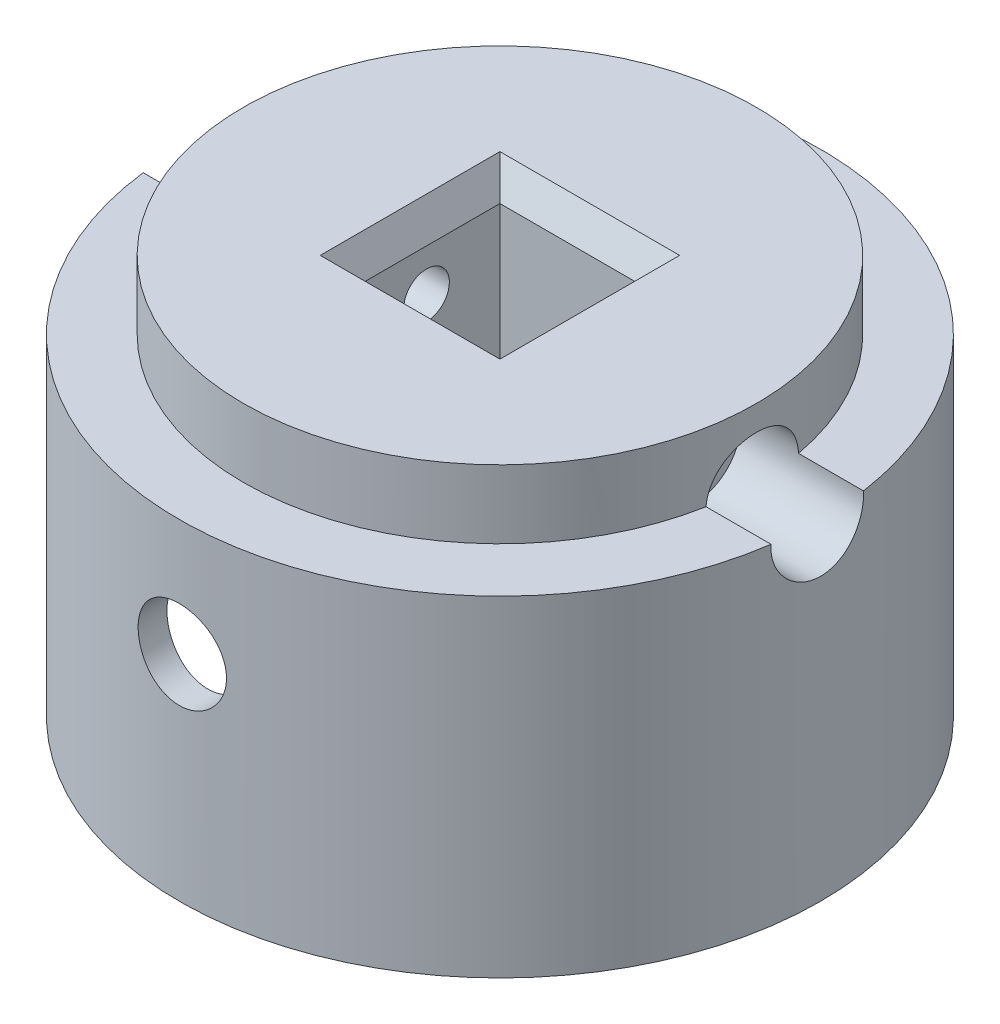
SolidWorks part; units mm, degrees
ref_plane "Спереди" through (0, 0, 0) normal (0, 0, 1) x (1, 0, 0)
ref_plane "Сверху" through (0, 0, 0) normal (0, 1, 0) x (1, 0, 0)
ref_plane "Справа" through (0, 0, 0) normal (1, 0, 0) x (0, 0, -1)
sketch "Sketch1" plane through (0, 0, 0) normal (0, 1, 0) x (1, 0, 0)
  circle A0 centre (0, 0) radius 22.5
  dimension "D1" = 45
extrude "Boss-Extrude1" add sketch "Sketch1" along normal blind 28
sketch "Sketch2" plane through (0, 0, 0) normal (0, -1, 0) x (1, 0, 0)
  line L1 (5.15, 5.15) -> (-5.15, 5.15)
  line L2 (5.15, 5.15) -> (5.15, -5.15)
  line L3 (5.15, -5.15) -> (-5.15, -5.15)
  line L4 (-5.15, 5.15) -> (-5.15, -5.15)
  line L5 (5.15, 5.15) -> (-5.15, -5.15) construction
  line L6 (5.15, -5.15) -> (-5.15, 5.15) construction
  point P0 (0, 0)
  dimension "D1" = 10.3
extrude "Cut-Extrude2" cut sketch "Sketch2" against normal through all
shell "Shell3" thickness 2
sketch "Sketch3" plane through (0, 0, 7.15) normal (0, 0, 1) x (1, 0, 0)
  line L0 (0, 26) -> (0, 0) construction
  line L1 (7.15, 26) -> (-7.15, 26) construction
  line L2 (7.15, 0) -> (-7.15, 0) construction
  line L3 (-22.5, 0) -> (22.5, 0) construction
  circle A0 centre (0, 15) radius 3.1
  dimension "D1" = 6.2
  dimension "D2" = 15
extrude "Cut-Extrude3" cut sketch "Sketch3" along normal through all
chamfer "Chamfer1" distance 2 angle 30 4 edges at (-5.15, 28, 0) (0, 28, 5.15) (5.15, 28, 0) (0, 28, -5.15)
sketch "Sketch18" plane through (0, 26, 0) normal (0, -1, 0) x (1, 0, 0)
  line L0 (0, 0) -> (-18.4253, -8.9866) construction
  line L1 (0, 0) -> (-17.385, 10.8633) construction
  line L2 (0, 0) -> (0, -20.5) construction
  line L3 (-15.7289, -7.6715) -> (-18.4253, -8.9866)
  line L4 (-14.8408, 9.2736) -> (-17.385, 10.8633)
  circle A0 centre (0, 0) radius 20.5 construction
  arc A1 (-18.4253, -8.9866) -> (-17.385, 10.8633) centre (0, 0) cw
  arc A2 (-14.8408, 9.2736) -> (-15.7289, -7.6715) centre (0, 0) ccw
  dimension "D1" = 64
  dimension "D2" = 58
  dimension "D3" = 3
extrude "Boss-Extrude8" add sketch "Sketch18" along normal offset from surface (23 mm away) 3 up to face at (0, 0, 20.5)
sketch "Sketch9" plane through (0, 0, 0) normal (0, -1, 0) x (1, 0, 0)
  line L0 (0, -7.15) -> (0, -20.5) construction
  line L2 (2.0571, -22.4058) -> (-16.5967, -15.1921)
  line L3 (-16.5967, -15.1921) -> (-17.6788, -17.9902)
  line L4 (-17.6788, -17.9902) -> (0.975, -25.2038)
  line L5 (0.975, -25.2038) -> (2.0571, -22.4058)
  line L6 (-7.15, -7.15) -> (7.15, -7.15) construction
  line L7 (2.0571, -22.4058) -> (0, -7.15) construction
  circle A0 centre (0, 0) radius 22.5 construction
  circle A1 centre (0, 0) radius 20.5 construction
  dimension "D1" = 20
  dimension "D2" = 3
  dimension "D3" = 7.679
extrude "Boss-Extrude4" add sketch "Sketch9" against normal blind 20
sketch "Sketch11" plane through (0, 0, 0) normal (0, -1, 0) x (1, 0, 0)
  line L0 (2.0571, -22.4058) -> (7.15, -7.15)
  line L1 (7.15, -7.15) -> (-7.15, -7.15)
  line L2 (-7.15, -7.15) -> (-16.5967, -15.1921)
  line L3 (-16.5967, -15.1921) -> (2.0571, -22.4058) construction
  line L4 (-3.78, -20.1485) -> (-10.7596, -17.4494) construction
  arc A0 (2.0571, -22.4058) -> (-16.5967, -15.1921) centre (0, 0) ccw construction
  arc A1 (2.0571, -22.4058) -> (-16.5967, -15.1921) centre (0, 0) cw
  arc A2 (2.0571, -22.4058) -> (-16.5967, -15.1921) centre (0, 0) ccw construction
  point P4 (-7.2698, -18.7989)
extrude "Boss-Extrude6" add sketch "Sketch11" against normal up to surface (26 mm away) up to face at (0, 26, 0)
sketch "Sketch12" plane through (0, 0, 0) normal (0, -1, 0) x (1, 0, 0)
  line L0 (-7.15, -7.15) -> (-15.0727, -13.8947) construction
  line L1 (2.7554, -20.314) -> (7.15, -7.15) construction
  line L2 (3.8359, -17.0772) -> (2.7554, -20.314)
  line L3 (-15.0727, -13.8947) -> (-12.7884, -11.95)
  arc A0 (2.7554, -20.314) -> (-15.0727, -13.8947) centre (0, 0) cw
  arc A1 (-12.7884, -11.95) -> (3.8359, -17.0772) centre (0, 0) ccw
  arc A2 (2.7554, -20.314) -> (-15.0727, -13.8947) centre (0, 0) ccw construction
  dimension "D1" = 3
extrude "Cut-Extrude5" cut sketch "Sketch12" against normal blind 12
sketch "Sketch13" plane through (-8.3519, 0, -21.597) normal (-0.3607, 0, -0.9327) x (-0.9327, 0, 0.3607)
  line L0 (0, 20) -> (0, 0) construction
  line L1 (10, 20) -> (-10, 20) construction
  line L2 (10, 0) -> (-10, 0) construction
  circle A0 centre (0, 10) radius 3.8
  dimension "D1" = 7.6
extrude "Cut-Extrude6" cut sketch "Sketch13" against normal blind 16
sketch "Sketch15" plane through (-8.3519, 0, -21.597) normal (-0.3607, 0, -0.9327) x (-0.9327, 0, 0.3607)
  line L0 (-10, 10) -> (10, 10) construction
  line L1 (-10, 20) -> (-10, 0) construction
  line L2 (10, 20) -> (10, 0) construction
  line L4 (5, 11.5) -> (-5, 11.5)
  line L5 (5, 11.5) -> (5, 8.5)
  line L6 (5, 8.5) -> (-5, 8.5)
  line L7 (-5, 11.5) -> (-5, 8.5)
  line L8 (5, 11.5) -> (-5, 8.5) construction
  line L9 (5, 8.5) -> (-5, 11.5) construction
  point P6 (0, 10)
  dimension "D1" = 10
  dimension "D2" = 3
extrude "Cut-Extrude8" cut sketch "Sketch15" against normal blind 16
sketch "Sketch17" plane through (0, 0, 0) normal (0, -1, 0) x (1, 0, 0)
  line L0 (7.15, 7.15) -> (7.15, -7.15)
  line L1 (7.15, -7.15) -> (3.8359, -17.0772)
  line L2 (7.15, 7.15) -> (-7.15, 7.15)
  line L3 (-7.15, 7.15) -> (-7.15, -7.15)
  line L4 (-7.15, -7.15) -> (-12.7884, -11.95)
  arc A0 (3.8359, -17.0772) -> (-12.7884, -11.95) centre (0, 0) cw
  arc A1 (-12.7884, -11.95) -> (3.8359, -17.0772) centre (0, 0) ccw construction
extrude "Cut-Extrude9" cut sketch "Sketch17" against normal blind 2
sketch "Sketch20" plane through (0, 26, 0) normal (0, -1, 0) x (1, 0, 0)
  line L0 (2.7554, -20.314) -> (7.15, -7.15)
  line L1 (7.15, -7.15) -> (7.15, 7.15)
  line L2 (7.15, 7.15) -> (-7.15, 7.15)
  line L3 (-7.15, 7.15) -> (-7.15, -7.15)
  line L4 (-7.15, -7.15) -> (-15.0727, -13.8947)
  arc A0 (2.7554, -20.314) -> (-15.0727, -13.8947) centre (0, 0) ccw
  arc A1 (2.7554, -20.314) -> (-17.385, 10.8633) centre (0, 0) ccw construction
extrude "Boss-Extrude10" add sketch "Sketch20" along normal blind 7
sketch "Sketch21" plane through (0, 28, 0) normal (0, 1, 0) x (1, 0, 0)
  circle A0 centre (0, 0) radius 18
  dimension "D1" = 36
extrude "Cut-Extrude11" cut sketch "Sketch21" against normal blind 4.8 flip side to cut
sketch "Sketch22" plane through (5.15, 0, 0) normal (-1, 0, 0) x (0, 0, 1)
  line L0 (0, 26) -> (0, 2) construction
  line L1 (5.15, 26) -> (-5.15, 26) construction
  line L2 (-5.15, 2) -> (5.15, 2) construction
  line L3 (-6.3047, 28) -> (6.3047, 28) construction
  circle A0 centre (0, 23) radius 1.6
  point P10 (0, 28)
  dimension "D1" = 3.2
  dimension "D2" = 5
extrude "Cut-Extrude12" cut sketch "Sketch22" against normal through all both and the other way through all
sketch "Sketch24" plane through (5.15, 0, 0) normal (-1, 0, 0) x (0, 0, 1)
  circle A0 centre (0, 23) radius 3.25
  dimension "D1" = 6.5
extrude "Cut-Extrude13" cut sketch "Sketch24" against normal through all from offset 8.5 offset against normal yes
sketch "Sketch25" plane through (-5.15, 0, 0) normal (1, 0, 0) x (0, 0, -1)
  line L0 (-5.15, 26) -> (-5.15, 2) construction
  line L1 (0, 19.8936) -> (2.6903, 21.4468)
  line L2 (2.6903, 21.4468) -> (2.6903, 24.5532)
  line L3 (2.6903, 24.5532) -> (0, 26.1064)
  line L4 (0, 26.1064) -> (-2.6903, 24.5532)
  line L5 (-2.6903, 24.5532) -> (-2.6903, 21.4468)
  line L6 (-2.6903, 21.4468) -> (0, 19.8936)
  circle A0 centre (0, 23) radius 3.1064 construction
extrude "Cut-Extrude14" cut sketch "Sketch25" against normal through all from offset 8.5
